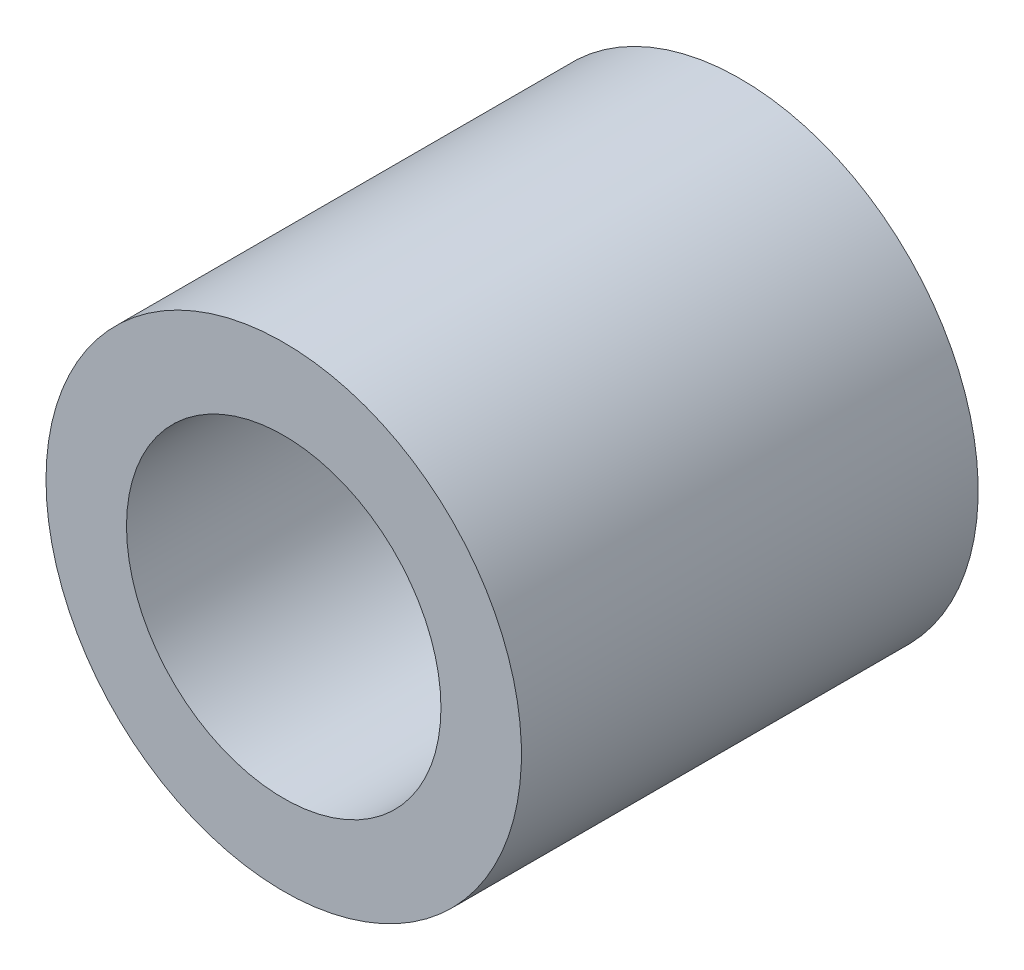
SolidWorks part; units mm, degrees
ref_plane "Alzado" through (0, 0, 0) normal (0, 0, 1) x (1, 0, 0)
ref_plane "Planta" through (0, 0, 0) normal (0, 1, 0) x (1, 0, 0)
ref_plane "Vista lateral" through (0, 0, 0) normal (1, 0, 0) x (0, 0, -1)
sketch "Croquis1" plane through (0, 0, 0) normal (0, 0, 1) x (1, 0, 0)
  circle A0 centre (0, 0) radius 5.25
  circle A1 centre (0, 0) radius 7.9375
  dimension "D1" = 10.5
  dimension "D2" = 15.875
extrude "Saliente-Extruir1" add sketch "Croquis1" along normal blind 15.25
